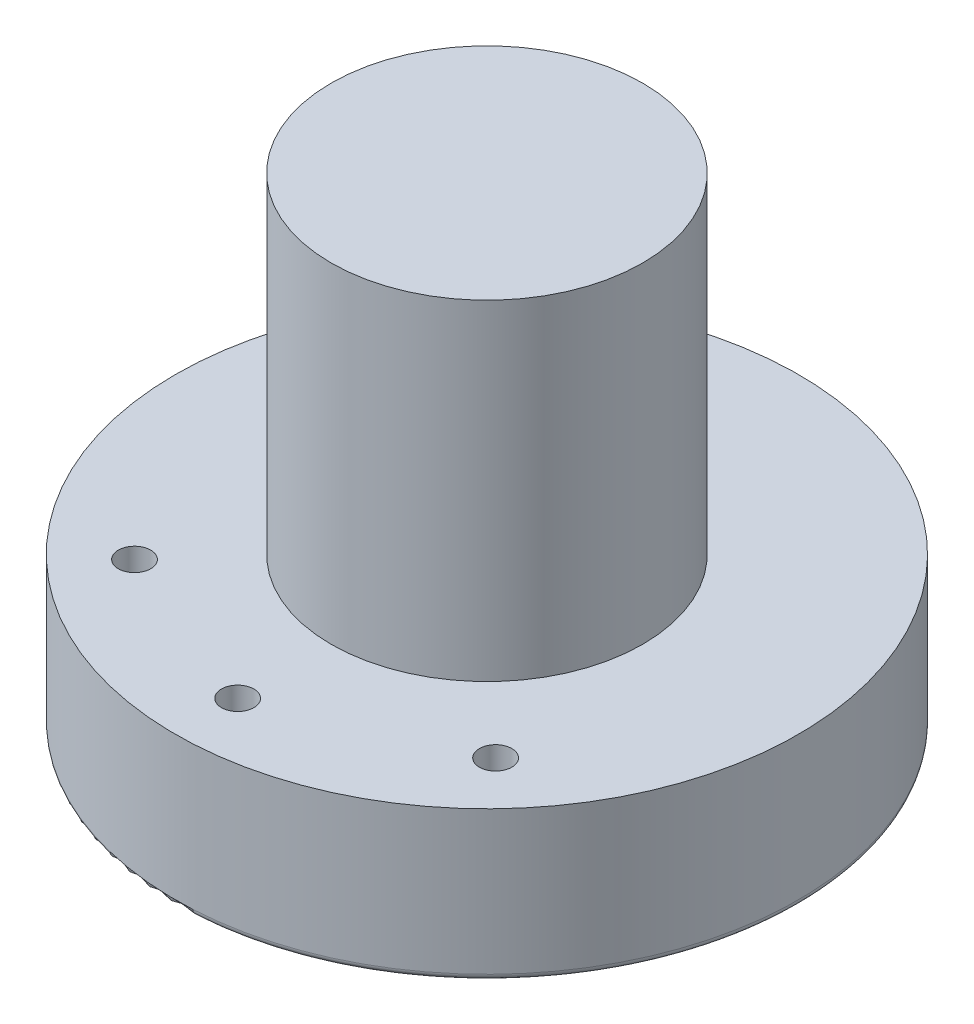
SolidWorks part; units mm, degrees
ref_plane "Front Plane" through (0, 0, 0) normal (0, 0, 1) x (1, 0, 0)
ref_plane "Top Plane" through (0, 0, 0) normal (0, 1, 0) x (1, 0, 0)
ref_plane "Right Plane" through (0, 0, 0) normal (1, 0, 0) x (0, 0, -1)
sketch "Sketch1" plane through (0, 0, 0) normal (0, 0, 1) x (1, 0, 0)
  line L0 (0, 0) -> (6, 0)
  line L1 (6, 0) -> (6, 1.5)
  line L2 (6, 1.5) -> (25, 1.5)
  line L3 (25, 1.5) -> (25, 13.5)
  line L4 (25, 13.5) -> (12.5, 13.5)
  line L5 (12.5, 13.5) -> (12.5, 40)
  line L6 (12.5, 40) -> (0, 40)
  line L7 (0, 40) -> (0, 0)
  dimension "D1" = 6
  dimension "D2" = 12
  dimension "D3" = 40
  dimension "D4" = 12.5
  dimension "D5" = 1.5
  dimension "D6" = 25
revolve "Revolve1" add sketch "Sketch1" angle 360 about L7
fillet "Fillet2" radius 0.5 2 edges at (-25, 1.5, 0) (-6, 0, 0)
hole_wizard "Ø1.0mm Dowel Hole1" positions "Sketch4" profile "Sketch3" hole size "Ø1.0" standard "ISO" end condition through all
sketch "Sketch4" plane through (0, 13.5, 0) normal (0, 1, 0) x (1, 0, 0)
  line L0 (0, 0) -> (14.4861, -13.7896) construction
  line L2 (0, 0) -> (-13.7896, -14.4861) construction
  circle A0 centre (0, 0) radius 20 construction
  point P0 (14.4861, -13.7896)
  point P2 (0, -20)
  point P4 (-13.7896, -14.4861)
  dimension "D1" = 40
  dimension "D2" = 90
sketch "Sketch3" plane through (14.4861, 13.5, 13.7896) normal (1, 0, 0) x (0, 0, 1)
  line L0 (0, 0) -> (0, 13.5)
  line L1 (0, 13.5) -> (1.3, 13.5)
  line L2 (1.3, 13.5) -> (1.3, 0)
  line L5 (1.3, 0) -> (0, 0)
  line L11 (0, -6.35) -> (0, 107.95) construction
  dimension "Thru Hole Dia." = 2.6
  dimension "Thru Hole Depth" = 13.5
